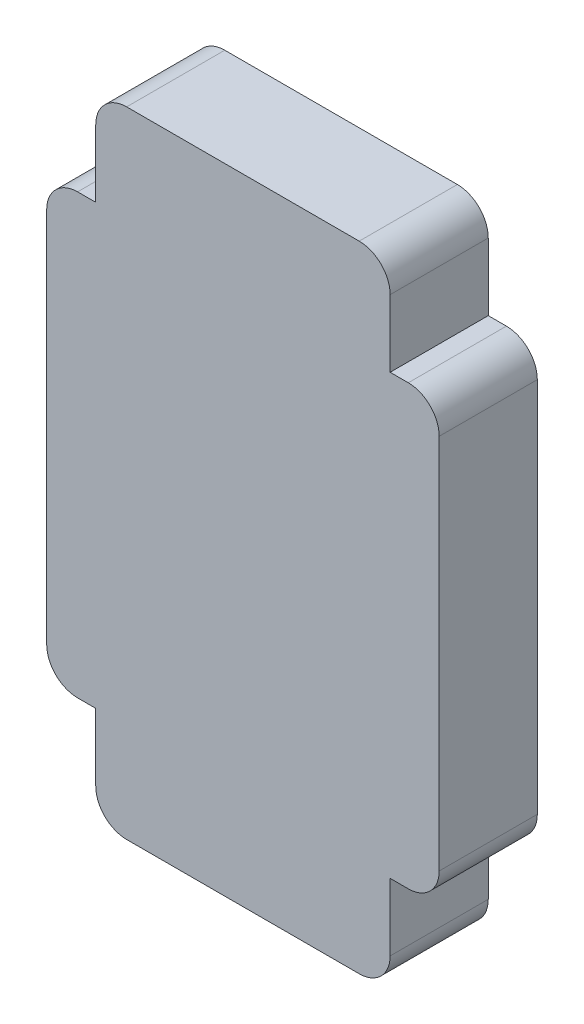
SolidWorks part; units mm, degrees
ref_plane "Front Plane" through (0, 0, 0) normal (0, 0, 1) x (1, 0, 0)
ref_plane "Top Plane" through (0, 0, 0) normal (0, 1, 0) x (1, 0, 0)
ref_plane "Right Plane" through (0, 0, 0) normal (1, 0, 0) x (0, 0, -1)
sketch "Sketch1" plane through (0, 0, 0) normal (0, 0, 1) x (1, 0, 0)
  line L0 (-4.7625, 7.09) -> (4.7625, 7.09)
  line L1 (-6.35, -7.09) -> (6.35, -7.09)
  line L2 (-6.35, -7.09) -> (-6.35, 7.09)
  line L3 (-6.35, 7.09) -> (6.35, 7.09)
  line L4 (6.35, -7.09) -> (6.35, 7.09)
  line L5 (-6.35, -7.09) -> (6.35, 7.09) construction
  line L6 (-6.35, 7.09) -> (6.35, -7.09) construction
  line L7 (-4.7625, 7.09) -> (-4.7625, 10.265)
  line L8 (4.7625, 7.09) -> (4.7625, 10.265)
  line L9 (-4.7625, 10.265) -> (4.7625, 10.265)
  line L10 (-4.7625, -7.09) -> (4.7625, -7.09)
  line L11 (-4.7625, -7.09) -> (-4.7625, -10.265)
  line L12 (4.7625, -7.09) -> (4.7625, -10.265)
  line L13 (-4.7625, -10.265) -> (4.7625, -10.265)
  point P0 (0, 0)
  point P6 (0, 10.265)
  dimension "D1" = 3.175
  dimension "D2" = 9.525
  dimension "D3" = 12.7
  dimension "D4" = 14.18
extrude "Boss-Extrude1" add sketch "Sketch1" along normal blind 3.175 contours L11 L13 L12 L1 | L1 L4 L3 L0 L2 | L9 L7 L0 L8
fillet "Fillet1" radius 1 8 edges at (6.35, -7.09, 1.5875) (4.7625, -10.265, 1.5875) (-6.35, -7.09, 1.5875) (-4.7625, -10.265, 1.5875) (-6.35, 7.09, 1.5875) (-4.7625, 10.265, 1.5875) (6.35, 7.09, 1.5875) (4.7625, 10.265, 1.5875)
